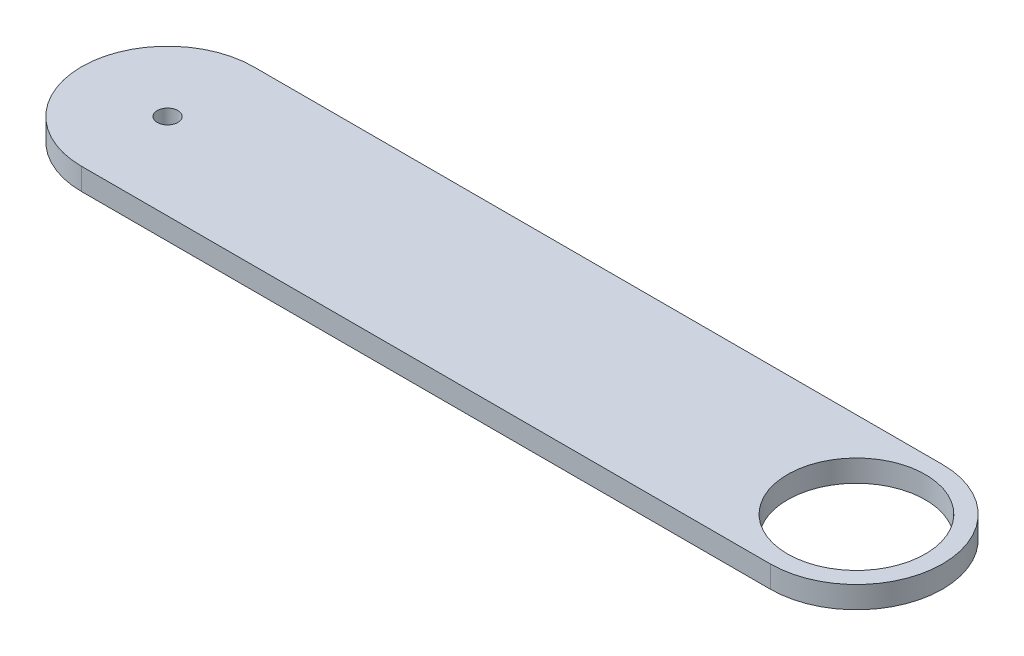
SolidWorks part; units mm, degrees
ref_plane "Front Plane" through (0, 0, 0) normal (0, 0, 1) x (1, 0, 0)
ref_plane "Top Plane" through (0, 0, 0) normal (0, 1, 0) x (1, 0, 0)
ref_plane "Right Plane" through (0, 0, 0) normal (1, 0, 0) x (0, 0, -1)
sketch "Sketch1" plane through (0, 0, 0) normal (0, 1, 0) x (1, 0, 0)
  line L0 (0, 0) -> (100, 0)
  line L1 (100, -25) -> (0, -25)
  line L2 (0, -12.5) -> (100, -12.5) construction
  arc A0 (0, 0) -> (0, -25) centre (0, -12.5) ccw
  arc A1 (100, -25) -> (100, 0) centre (100, -12.5) ccw
  dimension "D1" = 25
  dimension "D2" = 100
extrude "Boss-Extrude1" add sketch "Sketch1" along normal blind 3.18
sketch "Sketch2" plane through (0, 3.18, 0) normal (0, 1, 0) x (1, 0, 0)
  line L0 (-12.5, -12.5) -> (112.5, -12.5) construction
  line L1 (0, 0) -> (0, -25) construction
  line L2 (100, -25) -> (100, 0) construction
  circle A0 centre (0, -12.5) radius 1.5
  circle A1 centre (100, -12.5) radius 10
  arc A2 (0, 0) -> (0, -25) centre (0, -12.5) ccw construction
  arc A3 (100, -25) -> (100, 0) centre (100, -12.5) ccw construction
  dimension "D1" = 3
  dimension "D2" = 20
extrude "Cut-Extrude1" cut sketch "Sketch2" against normal blind 3.18
sketch "Sketch3" [suppressed] plane through (0, 0, 0) normal (0, -1, 0) x (1, 0, 0)
  circle A0 centre (-0.8919, 19.8964) radius 0.85 construction
  circle A1 centre (0.8919, 5.1036) radius 0.85 construction
  circle A2 centre (-0.8919, 19.8964) radius 0.85
  circle A3 centre (0.8919, 5.1036) radius 0.85
extrude "Cut-Extrude2" [suppressed] cut sketch "Sketch3" against normal up to next
